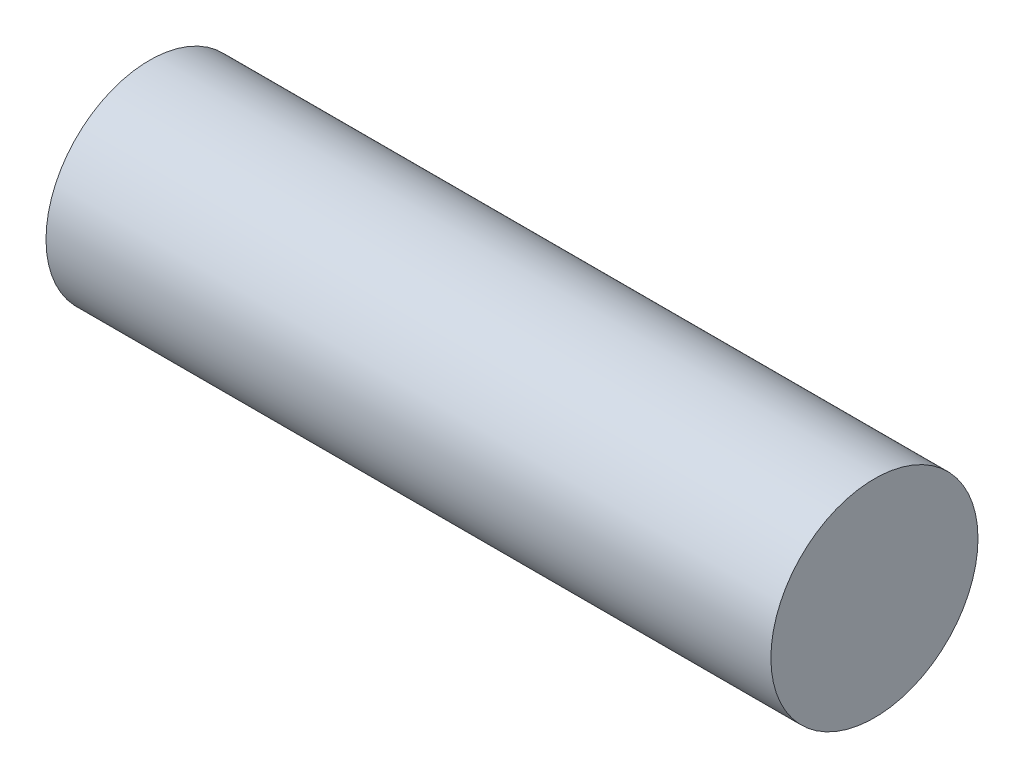
SolidWorks part; units mm, degrees
material "AISI Type A2 Tool Steel"
ref_plane "Front Plane" through (0, 0, 0) normal (1, 0, 0) x (0, 1, 0)
ref_plane "Top Plane" through (0, 0, 0) normal (0, 0, 1) x (0, 1, 0)
ref_plane "Right Plane" through (0, 0, 0) normal (0, 1, 0) x (-1, 0, 0)
sketch "Sketch1" plane through (0, 0, 0) normal (1, 0, 0) x (0, 1, 0)
  circle A0 centre (0, 0) radius 5
  dimension "D1" = 10
extrude "Boss-Extrude1" add sketch "Sketch1" along normal mid plane 35
